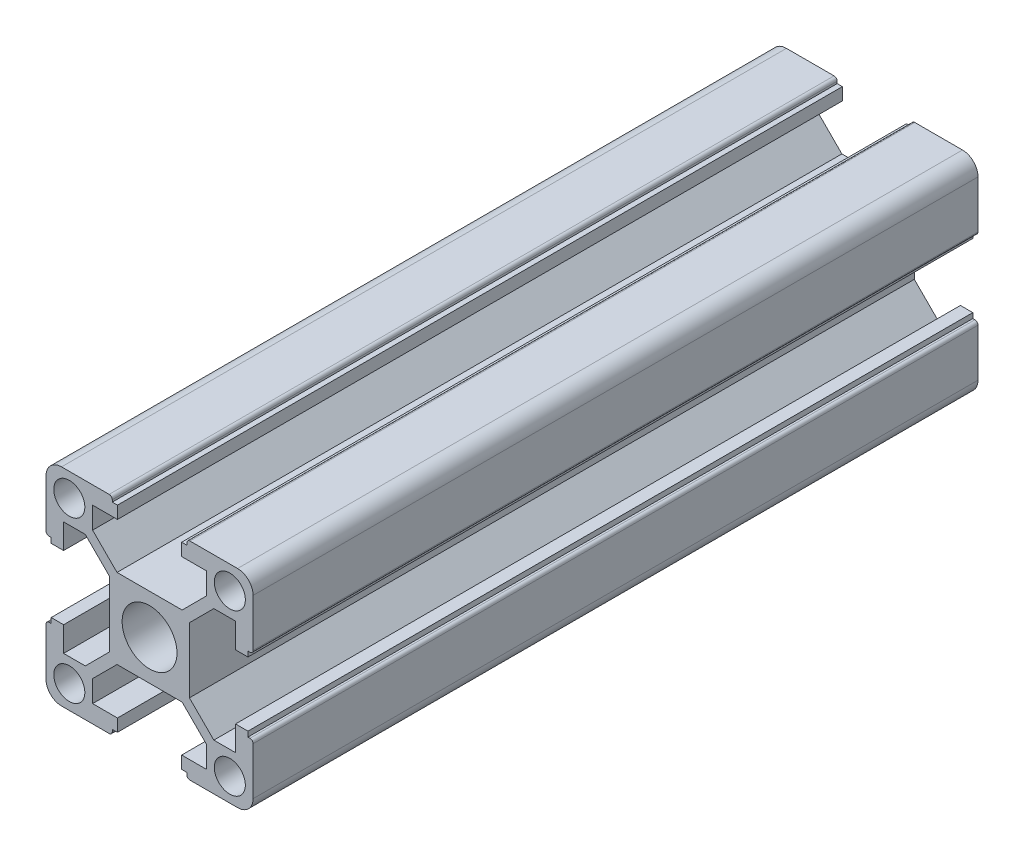
SolidWorks part; units mm, degrees
ref_plane "前视基准面" through (0, 0, 0) normal (0, 0, 1) x (1, 0, 0)
ref_plane "上视基准面" through (0, 0, 0) normal (0, 1, 0) x (1, 0, 0)
ref_plane "右视基准面" through (0, 0, 0) normal (1, 0, 0) x (0, 0, -1)
sketch "草图1" plane through (0, 0, 0) normal (0, 0, 1) x (1, 0, 0)
  line L0 (-7.75, 0) -> (0, 0) construction
  line L1 (7.75, -7.75) -> (-7.75, -7.75) construction
  line L2 (7.75, -7.75) -> (7.75, 7.75) construction
  line L3 (7.75, 7.75) -> (-7.75, 7.75) construction
  line L4 (-7.75, -7.75) -> (-7.75, 7.75) construction
  line L5 (7.75, -7.75) -> (-7.75, 7.75) construction
  line L6 (7.75, 7.75) -> (-7.75, -7.75) construction
  line L7 (0, 0) -> (0, 7.75) construction
  line L8 (3.1429, 3.85) -> (-3.1429, 3.85)
  line L9 (-3.1429, 3.85) -> (-5.5, 6.2071)
  line L10 (-5.5, 6.2071) -> (-5.5, 8.3)
  line L11 (-5.5, 8.3) -> (-3.1, 8.3)
  line L12 (-3.1, 8.3) -> (-3.1, 9.5)
  line L13 (-3.1, 9.5) -> (-3.6, 9.5)
  line L14 (-3.6, 9.5) -> (-3.6, 9.7)
  line L15 (-3.9, 10) -> (-8.5, 10)
  line L16 (-3.85, -3.1429) -> (-3.85, 3.1429)
  line L17 (-3.85, 3.1429) -> (-6.2071, 5.5)
  line L18 (-6.2071, 5.5) -> (-8.3, 5.5)
  line L19 (-8.3, 5.5) -> (-8.3, 3.1)
  line L20 (-9.5, 3.1) -> (-9.5, 3.6)
  line L21 (-8.3, 3.1) -> (-9.5, 3.1)
  line L22 (-9.5, 3.6) -> (-9.7, 3.6)
  line L23 (-10, 3.9) -> (-10, 8.5)
  line L24 (5.5, 8.3) -> (3.1, 8.3)
  line L25 (3.6, 9.5) -> (3.6, 9.7)
  line L26 (3.1, 9.5) -> (3.6, 9.5)
  line L27 (3.1, 8.3) -> (3.1, 9.5)
  line L28 (5.5, 6.2071) -> (5.5, 8.3)
  line L29 (3.1429, 3.85) -> (5.5, 6.2071)
  line L30 (3.85, -3.1429) -> (3.85, 3.1429)
  line L31 (3.85, 3.1429) -> (6.2071, 5.5)
  line L32 (9.5, 3.6) -> (9.7, 3.6)
  line L33 (8.3, 3.1) -> (9.5, 3.1)
  line L34 (9.5, 3.1) -> (9.5, 3.6)
  line L35 (8.3, 5.5) -> (8.3, 3.1)
  line L36 (6.2071, 5.5) -> (8.3, 5.5)
  line L37 (10, 3.9) -> (10, 8.5)
  line L38 (3.9, 10) -> (8.5, 10)
  line L39 (-9.5, -3.6) -> (-9.7, -3.6)
  line L40 (-8.3, -3.1) -> (-9.5, -3.1)
  line L41 (-9.5, -3.1) -> (-9.5, -3.6)
  line L42 (-8.3, -5.5) -> (-8.3, -3.1)
  line L43 (-6.2071, -5.5) -> (-8.3, -5.5)
  line L44 (-3.85, -3.1429) -> (-6.2071, -5.5)
  line L45 (-3.1429, -3.85) -> (-5.5, -6.2071)
  line L46 (-5.5, -6.2071) -> (-5.5, -8.3)
  line L47 (-3.6, -9.5) -> (-3.6, -9.7)
  line L48 (-3.1, -9.5) -> (-3.6, -9.5)
  line L49 (-3.1, -8.3) -> (-3.1, -9.5)
  line L50 (-5.5, -8.3) -> (-3.1, -8.3)
  line L51 (5.5, -6.2071) -> (5.5, -8.3)
  line L52 (3.1, -8.3) -> (3.1, -9.5)
  line L53 (3.1, -9.5) -> (3.6, -9.5)
  line L54 (3.6, -9.5) -> (3.6, -9.7)
  line L55 (5.5, -8.3) -> (3.1, -8.3)
  line L56 (3.1429, -3.85) -> (5.5, -6.2071)
  line L57 (3.1429, -3.85) -> (-3.1429, -3.85)
  line L58 (3.85, -3.1429) -> (6.2071, -5.5)
  line L59 (6.2071, -5.5) -> (8.3, -5.5)
  line L60 (8.3, -5.5) -> (8.3, -3.1)
  line L61 (9.5, -3.1) -> (9.5, -3.6)
  line L62 (8.3, -3.1) -> (9.5, -3.1)
  line L63 (9.5, -3.6) -> (9.7, -3.6)
  line L64 (3.9, -10) -> (8.5, -10)
  line L65 (10, -3.9) -> (10, -8.5)
  line L66 (-10, -3.9) -> (-10, -8.5)
  line L67 (-3.9, -10) -> (-8.5, -10)
  circle A0 centre (0, 0) radius 2.65
  circle A1 centre (-7.75, 7.75) radius 1.5
  circle A2 centre (7.75, 7.75) radius 1.5
  circle A3 centre (7.75, -7.75) radius 1.5
  circle A4 centre (-7.75, -7.75) radius 1.5
  arc A5 (-10, -8.5) -> (-8.5, -10) centre (-8.5, -8.5) ccw
  arc A6 (8.5, -10) -> (10, -8.5) centre (8.5, -8.5) ccw
  arc A7 (10, 8.5) -> (8.5, 10) centre (8.5, 8.5) ccw
  arc A8 (-8.5, 10) -> (-10, 8.5) centre (-8.5, 8.5) ccw
  arc A9 (3.6, -9.7) -> (3.9, -10) centre (3.9, -9.7) ccw
  arc A10 (-3.6, -9.7) -> (-3.9, -10) centre (-3.9, -9.7) cw
  arc A11 (-9.7, -3.6) -> (-10, -3.9) centre (-9.7, -3.9) ccw
  arc A12 (9.7, -3.6) -> (10, -3.9) centre (9.7, -3.9) cw
  arc A13 (9.7, 3.6) -> (10, 3.9) centre (9.7, 3.9) ccw
  arc A14 (-9.7, 3.6) -> (-10, 3.9) centre (-9.7, 3.9) cw
  arc A15 (3.6, 9.7) -> (3.9, 10) centre (3.9, 9.7) cw
  arc A16 (-3.6, 9.7) -> (-3.9, 10) centre (-3.9, 9.7) ccw
  point P46 (0, 3.85)
  point P56 (-3.85, 0)
  point P78 (3.85, 0)
  point P87 (-10, -10)
  point P90 (10, -10)
  point P93 (10, 10)
  point P96 (-10, 10)
  point P99 (3.6, -10)
  point P102 (-3.6, -10)
  point P105 (-10, -3.6)
  point P108 (10, -3.6)
  point P111 (10, 3.6)
  point P114 (-10, 3.6)
  point P117 (3.6, 10)
  point P120 (-3.6, 10)
  dimension "D1" = 5.3
  dimension "D2" = 3
  dimension "D11" = 1.5
  dimension "D12" = 2.25
  dimension "D13" = 0.3
  dimension "D3" = 7.7
  dimension "D4" = 6.2
  dimension "D5" = 1.7
  dimension "D6" = 1.2
  dimension "D7" = 20
  dimension "D8" = 7.2
  dimension "D9" = 11
  dimension "D10" = 1
extrude "凸台-拉伸1" add sketch "草图1" along normal mid plane 70
sketch "草图5" plane through (0, 0, 0) normal (1, 0, 0) x (0, 0, -1)
  line L0 (35, 3.1429) -> (35, -3.1429) construction
  circle A0 centre (25, 0) radius 2
  dimension "D1" = 4
  dimension "D2" = 10
extrude "切除-拉伸3" cut sketch "草图5" against normal through all both and the other way through all
sketch "草图6" plane through (-3.85, 0, 0) normal (-1, 0, 0) x (0, 0, 1)
  circle A0 centre (-25, 0) radius 4.25
  dimension "D1" = 8.5
extrude "切除-拉伸4" cut sketch "草图6" along normal through all
